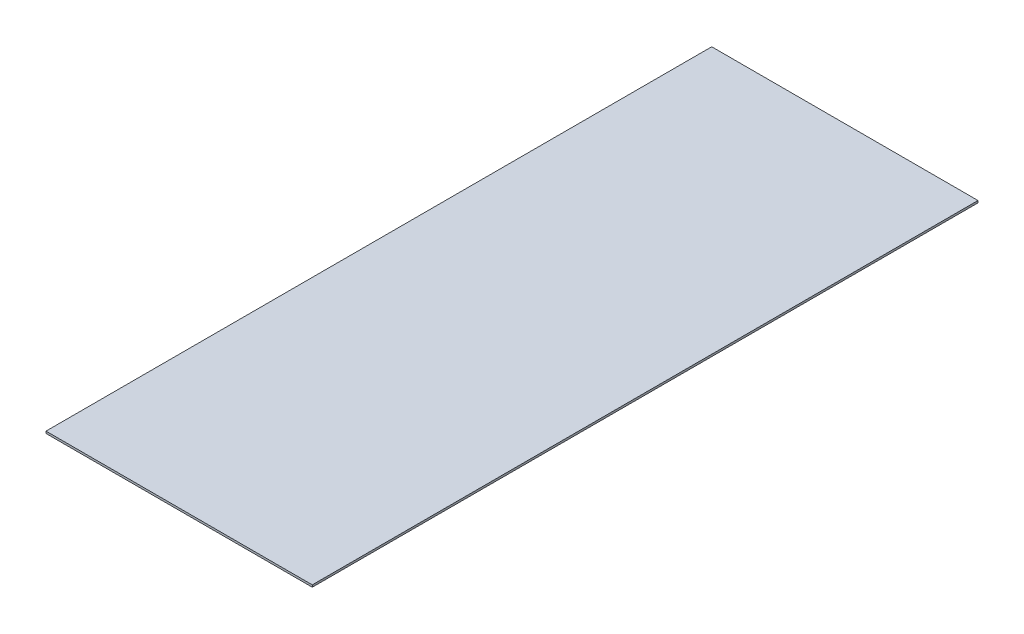
SolidWorks part; units mm, degrees
material "ASTM A36 Acero"
ref_plane "Alzado" through (0, 0, 0) normal (0, 0, 1) x (1, 0, 0)
ref_plane "Planta" through (0, 0, 0) normal (0, 1, 0) x (1, 0, 0)
ref_plane "Vista lateral" through (0, 0, 0) normal (1, 0, 0) x (0, 0, -1)
sketch "Croquis1" plane through (0, 0, 0) normal (0, 1, 0) x (1, 0, 0)
  line L1 (-609.6, -1524) -> (609.6, -1524)
  line L2 (-609.6, -1524) -> (-609.6, 1524)
  line L3 (-609.6, 1524) -> (609.6, 1524)
  line L4 (609.6, -1524) -> (609.6, 1524)
  line L5 (-609.6, -1524) -> (609.6, 1524) construction
  line L6 (-609.6, 1524) -> (609.6, -1524) construction
  point P0 (0, 0)
  dimension "D1" = 3048
  dimension "D2" = 1219.2
extrude "Saliente-Extruir1" add sketch "Croquis1" along normal blind 9.5
